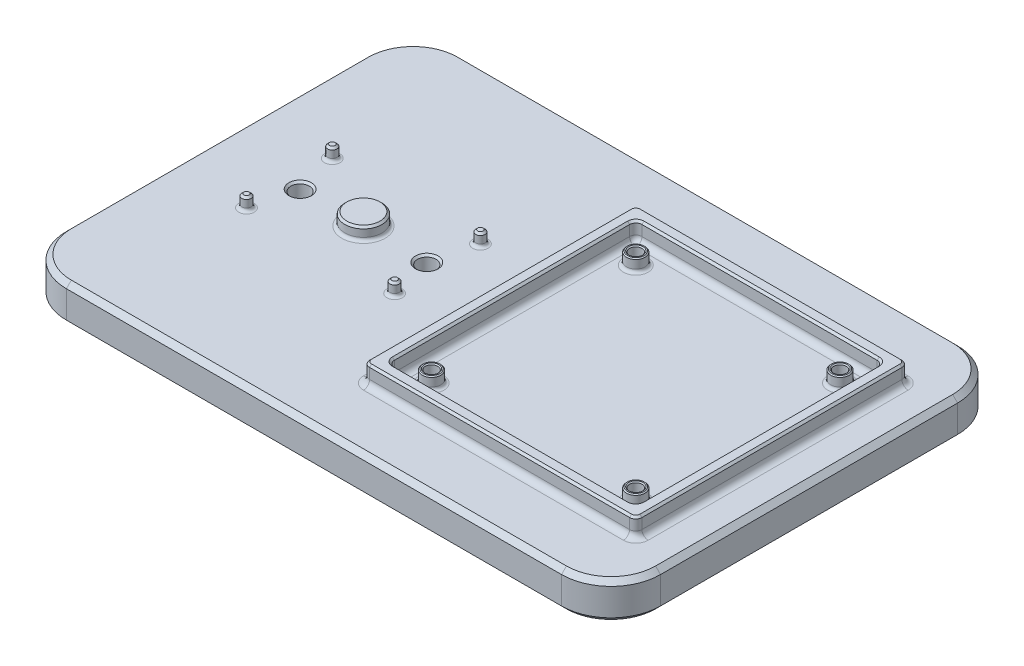
SolidWorks part; units mm, degrees
ref_plane "Front" through (0, 0, 0) normal (0, 0, 1) x (1, 0, 0)
ref_plane "Top" through (0, 0, 0) normal (0, 1, 0) x (1, 0, 0)
ref_plane "Right" through (0, 0, 0) normal (1, 0, 0) x (0, 0, -1)
sketch "Sketch2" plane through (0, 0, 0) normal (0, 1, 0) x (1, 0, 0)
  line L0 (5.5563, 26.1938) -> (57.9438, 26.1937) construction
  line L1 (-76.2, -50.8) -> (76.2, -50.8)
  line L2 (-76.2, -50.8) -> (-76.2, 50.8)
  line L3 (-76.2, 50.8) -> (76.2, 50.8)
  line L4 (76.2, -50.8) -> (76.2, 50.8)
  line L5 (-76.2, -50.8) -> (76.2, 50.8) construction
  line L6 (-76.2, 50.8) -> (76.2, -50.8) construction
  line L7 (57.9438, 26.1937) -> (57.9438, -26.1938) construction
  line L8 (57.9438, -26.1938) -> (5.5563, -26.1938) construction
  line L9 (5.5563, -26.1938) -> (5.5563, 26.1938) construction
  line L10 (57.9438, 0) -> (76.2, 0) construction
  line L11 (-38.1, 0) -> (-21.85, 0) construction
  line L12 (-54.35, 0) -> (-38.1, 0) construction
  circle A0 centre (57.9438, 26.1937) radius 1.5875
  circle A1 centre (57.9438, -26.1938) radius 1.5875
  circle A2 centre (5.5563, -26.1938) radius 1.5875
  circle A3 centre (5.5563, 26.1938) radius 1.5875
  circle A5 centre (-54.35, 0) radius 2.3812
  circle A6 centre (-21.85, 0) radius 2.3813
  point P0 (0, 0)
  dimension "D5" = 3.175
  dimension "D8" = 4.7625
  dimension "D1" = 101.6
  dimension "D2" = 152.4
  dimension "D3" = 18.2562
  dimension "D4" = 52.3875
  dimension "D7" = 38.1
  dimension "D9" = 21.85
extrude "Boss-Extrude1" add sketch "Sketch2" along normal blind 9.525
sketch "Sketch3" plane through (0, 9.525, 0) normal (0, 1, 0) x (1, 0, 0)
  line L0 (-54.35, 0) -> (-38.1, 0) construction
  line L1 (-38.1, 0) -> (-21.85, 0) construction
  line L2 (-19.1, 11) -> (-57.1, 11) construction
  line L3 (-57.1, -11) -> (-57.1, 11) construction
  line L4 (-57.1, -11) -> (-19.1, -11) construction
  line L5 (-19.1, 11) -> (-19.1, -11) construction
  line L6 (-38.1, 0) -> (-38.1, 11) construction
  line L7 (-38.1, 0) -> (-38.1, -11) construction
  circle A0 centre (-38.1, 0) radius 4.7625
  circle A1 centre (-57.1, 11) radius 1.1906
  circle A2 centre (-19.1, 11) radius 1.1906
  circle A3 centre (-57.1, -11) radius 1.1906
  circle A4 centre (-19.1, -11) radius 1.1906
  circle A5 centre (5.5563, 26.1938) radius 2.3813
  circle A6 centre (57.9438, 26.1937) radius 2.3812
  circle A7 centre (57.9438, -26.1938) radius 2.3812
  circle A8 centre (5.5563, -26.1938) radius 2.3813
  circle A9 centre (5.5563, 26.1938) radius 1.5875 construction
  circle A10 centre (57.9438, -26.1938) radius 1.5875 construction
  circle A11 centre (5.5563, -26.1938) radius 1.5875 construction
  circle A12 centre (57.9438, 26.1937) radius 1.5875 construction
  circle A13 centre (57.9438, -26.1938) radius 1.5875
  circle A14 centre (5.5563, -26.1938) radius 1.5875
  circle A15 centre (5.5563, 26.1938) radius 1.5875
  circle A16 centre (57.9438, 26.1937) radius 1.5875
  dimension "D1" = 9.525
  dimension "D4" = 2.3813
  dimension "D5" = 4.7625
  dimension "D2" = 11
  dimension "D3" = 19
extrude "Boss-Extrude2" add sketch "Sketch3" along normal blind 3.175
sketch "Sketch5" plane through (0, 9.525, 0) normal (0, 1, 0) x (1, 0, 0)
  line L0 (-3.175, 34.925) -> (66.675, 34.925)
  line L1 (0, -31.75) -> (63.5, -31.75)
  line L2 (0, -31.75) -> (0, 31.75)
  line L3 (0, 31.75) -> (63.5, 31.75)
  line L4 (63.5, -31.75) -> (63.5, 31.75)
  line L5 (0, -31.75) -> (63.5, 31.75) construction
  line L6 (0, 31.75) -> (63.5, -31.75) construction
  line L7 (66.675, -34.925) -> (66.675, 34.925)
  line L8 (-3.175, -34.925) -> (66.675, -34.925)
  line L9 (-3.175, -34.925) -> (-3.175, 34.925)
  line L10 (5.5563, 26.1938) -> (57.9438, 26.1937) construction
  line L11 (0.7938, -30.9562) -> (62.7063, -30.9562) construction
  line L12 (0.7938, -30.9562) -> (0.7938, 30.9563) construction
  line L13 (0.7938, 30.9563) -> (62.7063, 30.9563) construction
  line L14 (62.7063, -30.9562) -> (62.7063, 30.9563) construction
  line L15 (0.7938, -30.9562) -> (62.7063, 30.9563) construction
  line L16 (0.7938, 30.9563) -> (62.7063, -30.9562) construction
  point P0 (31.75, 0)
  point P7 (31.75, 0)
  dimension "D2" = 0.7937
  dimension "D3" = 61.9125
  dimension "D1" = 3.175
extrude "Boss-Extrude4" add sketch "Sketch5" along normal blind 4.7625
sketch "Sketch6" plane through (0, 0, 0) normal (0, -1, 0) x (1, 0, 0)
  line L1 (-51.6004, 4.7625) -> (-57.0996, 4.7625)
  line L2 (-57.0996, 4.7625) -> (-59.8493, 0)
  line L3 (-59.8493, 0) -> (-57.0996, -4.7625)
  line L4 (-57.0996, -4.7625) -> (-51.6004, -4.7625)
  line L5 (-51.6004, -4.7625) -> (-48.8507, 0)
  line L6 (-48.8507, 0) -> (-51.6004, 4.7625)
  line L7 (-19.1004, 4.7625) -> (-24.5996, 4.7625)
  line L8 (-24.5996, 4.7625) -> (-27.3493, 0)
  line L9 (-27.3493, 0) -> (-24.5996, -4.7625)
  line L10 (-24.5996, -4.7625) -> (-19.1004, -4.7625)
  line L11 (-19.1004, -4.7625) -> (-16.3507, 0)
  line L12 (-16.3507, 0) -> (-19.1004, 4.7625)
  circle A0 centre (-54.35, 0) radius 4.7625 construction
  circle A1 centre (-21.85, 0) radius 4.7625 construction
  dimension "D1" = 9.525
extrude "Cut-Extrude1" cut sketch "Sketch6" against normal blind 3.175
sketch "Sketch7" plane through (0, 0, 0) normal (0, -1, 0) x (1, 0, 0)
  line L1 (7.426, 29.4323) -> (3.6865, 29.4323)
  line L2 (3.6865, 29.4323) -> (1.8168, 26.1938)
  line L3 (1.8168, 26.1938) -> (3.6865, 22.9553)
  line L4 (3.6865, 22.9553) -> (7.426, 22.9553)
  line L5 (7.426, 22.9553) -> (9.2957, 26.1938)
  line L6 (9.2957, 26.1938) -> (7.426, 29.4323)
  line L7 (59.8135, 29.4323) -> (56.074, 29.4322)
  line L8 (56.074, 29.4322) -> (54.2043, 26.1937)
  line L9 (54.2043, 26.1937) -> (56.074, 22.9553)
  line L10 (56.074, 22.9553) -> (59.8135, 22.9552)
  line L11 (59.8135, 22.9552) -> (61.6832, 26.1937)
  line L12 (61.6832, 26.1937) -> (59.8135, 29.4323)
  line L13 (7.426, -22.9553) -> (3.6865, -22.9553)
  line L14 (3.6865, -22.9553) -> (1.8168, -26.1938)
  line L15 (1.8168, -26.1938) -> (3.6865, -29.4323)
  line L16 (3.6865, -29.4323) -> (7.426, -29.4323)
  line L17 (7.426, -29.4323) -> (9.2957, -26.1938)
  line L18 (9.2957, -26.1938) -> (7.426, -22.9553)
  line L19 (59.8135, -22.9552) -> (56.074, -22.9552)
  line L20 (56.074, -22.9552) -> (54.2043, -26.1938)
  line L21 (54.2043, -26.1938) -> (56.074, -29.4322)
  line L22 (56.074, -29.4322) -> (59.8135, -29.4322)
  line L23 (59.8135, -29.4322) -> (61.6832, -26.1937)
  line L24 (61.6832, -26.1937) -> (59.8135, -22.9552)
  circle A0 centre (5.5563, 26.1938) radius 3.2385 construction
  circle A1 centre (57.9438, 26.1938) radius 3.2385 construction
  circle A2 centre (5.5563, -26.1938) radius 3.2385 construction
  circle A3 centre (57.9438, -26.1937) radius 3.2385 construction
  dimension "D1" = 6.477
extrude "Cut-Extrude2" cut sketch "Sketch7" against normal blind 2.3813
fillet "Fillet2" radius 12.7 4 edges at (76.2, 4.7625, 50.8) (-76.2, 4.7625, -50.8) (76.2, 4.7625, -50.8) (-76.2, 4.7625, 50.8)
fillet "Fillet4" radius 1.5875 16 edges at (0, 11.9062, 31.75) (31.75, 9.525, 31.75) (0, 9.525, 0) (63.5, 9.525, 0) (31.75, 9.525, -31.75) (63.5, 11.9062, -31.75) (63.5, 11.9062, 31.75) (0, 11.9062, -31.75) (-3.175, 11.9062, -34.925) (66.675, 11.9062, -34.925) (66.675, 11.9062, 34.925) (-3.175, 11.9062, 34.925) (66.675, 9.525, 0) (31.75, 9.525, -34.925) (-3.175, 9.525, 0) (31.75, 9.525, 34.925)
fillet "Fillet5" radius 0.7937 5 edges at (-38.1, 9.525, -4.7625) (5.5563, 9.525, -28.575) (57.9438, 9.525, -28.575) (57.9438, 9.525, 23.8125) (5.5563, 9.525, 23.8125)
fillet "Fillet6" radius 0.7937 76 edges at (9.2957, 1.1906, 26.1938) (1.8168, 1.1906, 26.1938) (3.6865, 1.1906, 29.4323) (7.426, 1.1906, 29.4323) (7.426, 1.1906, 22.9553) (2.7516, 2.3813, 24.5745) (2.7516, 2.3813, 27.813) (5.5563, 2.3813, 29.4323) (8.3609, 2.3813, 27.813) (8.3609, 2.3813, 24.5745) (3.6865, 1.1906, 22.9553) (5.5563, 2.3813, 22.9553) (-57.1, 9.525, -12.1906) (-57.1, 9.525, 9.8094) (-19.1, 9.525, 9.8094) (-19.1, 9.525, -12.1906) (7.426, 1.1906, -29.4323) (3.6865, 1.1906, -29.4323) (1.8168, 1.1906, -26.1938) (3.6865, 1.1906, -22.9553) (7.426, 1.1906, -22.9553) (9.2957, 1.1906, -26.1938) (8.3609, 2.3813, -27.813) (5.5563, 2.3813, -29.4323) (2.7516, 2.3813, -27.813) (2.7516, 2.3813, -24.5745) (5.5563, 2.3813, -22.9553) (8.3609, 2.3813, -24.5745) (59.8135, 1.1906, -29.4322) (56.074, 1.1906, -29.4322) (54.2043, 1.1906, -26.1938) (56.074, 1.1906, -22.9552) (59.8135, 1.1906, -22.9552) (61.6832, 1.1906, -26.1937) (60.7484, 2.3813, -27.813) (57.9438, 2.3813, -29.4322) (55.1391, 2.3813, -27.813) (55.1391, 2.3813, -24.5745) (57.9438, 2.3813, -22.9552) (60.7484, 2.3813, -24.5745) (60.7484, 2.3813, 24.5745) (57.9438, 2.3813, 22.9552) (55.1391, 2.3813, 24.5745) (55.1391, 2.3813, 27.813) (57.9438, 2.3813, 29.4322) (60.7484, 2.3813, 27.813) (59.8135, 1.1906, 22.9552) (56.074, 1.1906, 22.9553) (54.2043, 1.1906, 26.1937) (56.074, 1.1906, 29.4322) (59.8135, 1.1906, 29.4323) (61.6832, 1.1906, 26.1937) (-19.1004, 1.5875, -4.7625) (-24.5996, 1.5875, -4.7625) (-27.3493, 1.5875, 0) (-24.5996, 1.5875, 4.7625) (-19.1004, 1.5875, 4.7625) (-16.3507, 1.5875, 0) (-17.7256, 3.175, -2.3812) (-21.85, 3.175, -4.7625) (-25.9745, 3.175, -2.3813) (-25.9745, 3.175, 2.3812) (-21.85, 3.175, 4.7625) (-17.7256, 3.175, 2.3813) (-51.6004, 1.5875, -4.7625) (-57.0996, 1.5875, -4.7625) (-59.8493, 1.5875, 0) (-57.0996, 1.5875, 4.7625) (-51.6004, 1.5875, 4.7625) (-48.8507, 1.5875, 0) (-50.2255, 3.175, -2.3812) (-54.35, 3.175, -4.7625) (-58.4744, 3.175, -2.3812) (-58.4744, 3.175, 2.3813) (-54.35, 3.175, 4.7625) (-50.2255, 3.175, 2.3813)
chamfer "Chamfer1" distance 1.27 angle 45 16 edges at (76.2, 0, 0) (72.4803, 0, -47.0803) (72.4803, 0, 47.0803) (0, 0, -50.8) (0, 0, 50.8) (-72.4803, 0, -47.0803) (-72.4803, 0, 47.0803) (-76.2, 0, 0) (76.2, 9.525, 0) (72.4803, 9.525, -47.0803) (72.4803, 9.525, 47.0803) (0, 9.525, -50.8) (0, 9.525, 50.8) (-72.4803, 9.525, -47.0803) (-72.4803, 9.525, 47.0803) (-76.2, 9.525, 0)
chamfer "Chamfer2" distance 0.508 angle 45 49 edges at (63.035, 14.2875, -31.285) (31.75, 14.2875, -31.75) (0.465, 14.2875, -31.285) (0, 14.2875, 0) (0.465, 14.2875, 31.285) (31.75, 14.2875, 31.75) (63.035, 14.2875, 31.285) (63.5, 14.2875, 0) (66.21, 14.2875, -34.46) (66.675, 14.2875, 0) (66.21, 14.2875, 34.46) (31.75, 14.2875, 34.925) (-2.71, 14.2875, 34.46) (-3.175, 14.2875, 0) (-2.71, 14.2875, -34.46) (31.75, 14.2875, -34.925) (-57.1, 12.7, -9.8094) (-57.1, 12.7, 12.1906) (-19.1, 12.7, -9.8094) (-19.1, 12.7, 12.1906) (-38.1, 12.7, 4.7625) (-54.35, 3.175, -2.3812) (-54.35, 9.525, 2.3812) (-21.85, 3.175, -2.3813) (-21.85, 9.525, 2.3813) (-21.85, 0, -4.7625) (-19.1618, 0, -4.6562) (-24.5382, 0, -4.6562) (-17.7256, 0, -2.3812) (-25.9745, 0, -2.3813) (-16.4735, 0, 0) (-27.2265, 0, 0) (-17.7256, 0, 2.3813) (-25.9745, 0, 2.3812) (-19.1618, 0, 4.6562) (-24.5382, 0, 4.6562) (-21.85, 0, 4.7625) (-54.35, 0, -4.7625) (-51.6618, 0, -4.6562) (-57.0382, 0, -4.6562) (-50.2255, 0, -2.3812) (-58.4744, 0, -2.3812) (-48.9735, 0, 0) (-59.7265, 0, 0) (-50.2255, 0, 2.3813) (-58.4744, 0, 2.3813) (-51.6618, 0, 4.6562) (-57.0382, 0, 4.6562) (-54.35, 0, 4.7625)
chamfer "Chamfer3" distance 0.254 angle 45 60 edges at (5.5563, 2.3812, -27.7813) (5.5563, 12.7, -24.6063) (5.5563, 2.3812, 24.6063) (5.5563, 12.7, 27.7813) (57.9438, 2.3812, 24.6063) (57.9438, 12.7, 27.7812) (57.9438, 2.3812, -27.7812) (57.9438, 12.7, -24.6062) (5.5563, 12.7, -23.8125) (5.5563, 12.7, 28.575) (57.9438, 12.7, 28.575) (57.9438, 12.7, -23.8125) (5.5563, 0, 22.9553) (7.3646, 0, 23.0616) (3.7479, 0, 23.0616) (8.3609, 0, 24.5745) (2.7516, 0, 24.5745) (9.173, 0, 26.1938) (1.9395, 0, 26.1938) (8.3609, 0, 27.813) (2.7516, 0, 27.813) (7.3646, 0, 29.3259) (3.7479, 0, 29.3259) (5.5563, 0, 29.4323) (57.9438, 0, 22.9552) (59.7521, 0, 23.0616) (56.1354, 0, 23.0616) (60.7484, 0, 24.5745) (55.1391, 0, 24.5745) (61.5605, 0, 26.1937) (54.327, 0, 26.1937) (60.7484, 0, 27.813) (55.1391, 0, 27.813) (59.7521, 0, 29.3259) (56.1354, 0, 29.3259) (57.9438, 0, 29.4322) (5.5563, 0, -29.4323) (7.3646, 0, -29.3259) (3.7479, 0, -29.3259) (8.3609, 0, -27.813) (2.7516, 0, -27.813) (9.173, 0, -26.1938) (1.9395, 0, -26.1938) (8.3609, 0, -24.5745) (2.7516, 0, -24.5745) (7.3646, 0, -23.0616) (3.7479, 0, -23.0616) (5.5563, 0, -22.9553) (57.9438, 0, -29.4322) (59.7521, 0, -29.3259) (56.1354, 0, -29.3259) (60.7484, 0, -27.813) (55.1391, 0, -27.813) (61.5605, 0, -26.1937) (54.327, 0, -26.1938) (60.7484, 0, -24.5745) (55.1391, 0, -24.5745) (59.7521, 0, -23.0616) (56.1354, 0, -23.0616) (57.9438, 0, -22.9552)
